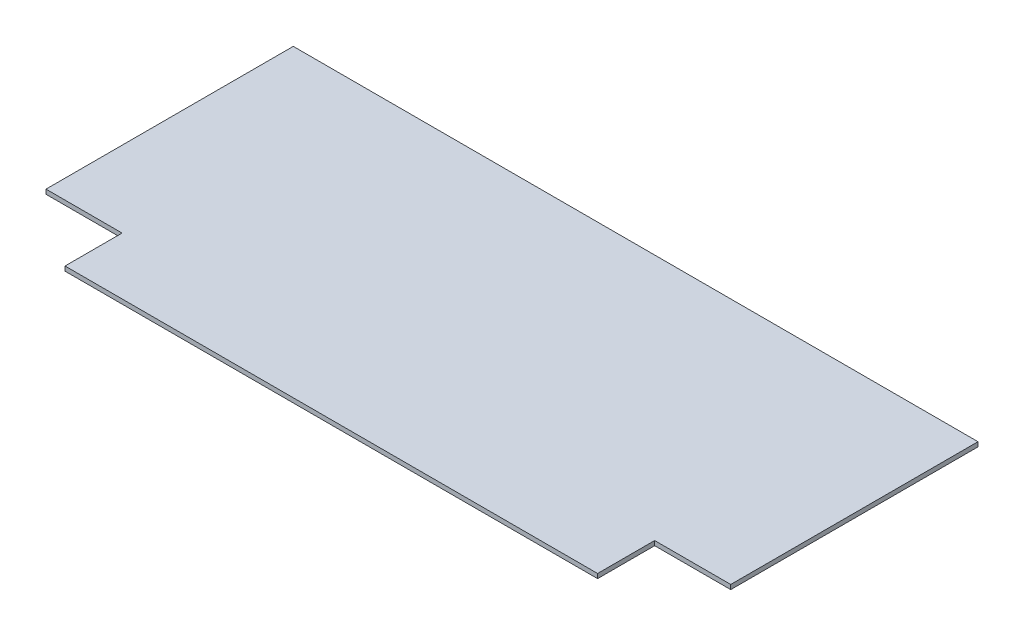
SolidWorks part; units mm, degrees
ref_plane "Front Plane" through (0, 0, 0) normal (0, 0, 1) x (1, 0, 0)
ref_plane "Top Plane" through (0, 0, 0) normal (0, 1, 0) x (1, 0, 0)
ref_plane "Right Plane" through (0, 0, 0) normal (1, 0, 0) x (0, 0, -1)
sketch "Sketch1" plane through (0, 0, 0) normal (0, 1, 0) x (1, 0, 0)
  line L1 (228.6, -101.6) -> (-228.6, -101.6)
  line L2 (228.6, -101.6) -> (228.6, 101.6)
  line L3 (228.6, 101.6) -> (-228.6, 101.6)
  line L4 (-228.6, -101.6) -> (-228.6, 101.6)
  line L5 (228.6, -101.6) -> (-228.6, 101.6) construction
  line L6 (228.6, 101.6) -> (-228.6, -101.6) construction
  point P0 (0, 0)
  dimension "D1" = 457.2
  dimension "D2" = 203.2
extrude "Boss-Extrude1" add sketch "Sketch1" along normal blind 3
sketch "Sketch2" plane through (0, 3, 0) normal (0, 1, 0) x (1, 0, 0)
  line L1 (-228.6, -101.6) -> (-177.8, -101.6)
  line L2 (-228.6, -101.6) -> (-228.6, -63.5)
  line L3 (-228.6, -63.5) -> (-177.8, -63.5)
  line L4 (-177.8, -101.6) -> (-177.8, -63.5)
  line L5 (228.6, -101.6) -> (177.8, -101.6)
  line L6 (228.6, -101.6) -> (228.6, -63.5)
  line L7 (228.6, -63.5) -> (177.8, -63.5)
  line L8 (177.8, -101.6) -> (177.8, -63.5)
  dimension "D1" = 50.8
  dimension "D2" = 38.1
  dimension "D3" = 38.1
  dimension "D4" = 50.8
extrude "Cut-Extrude1" cut sketch "Sketch2" against normal through all
